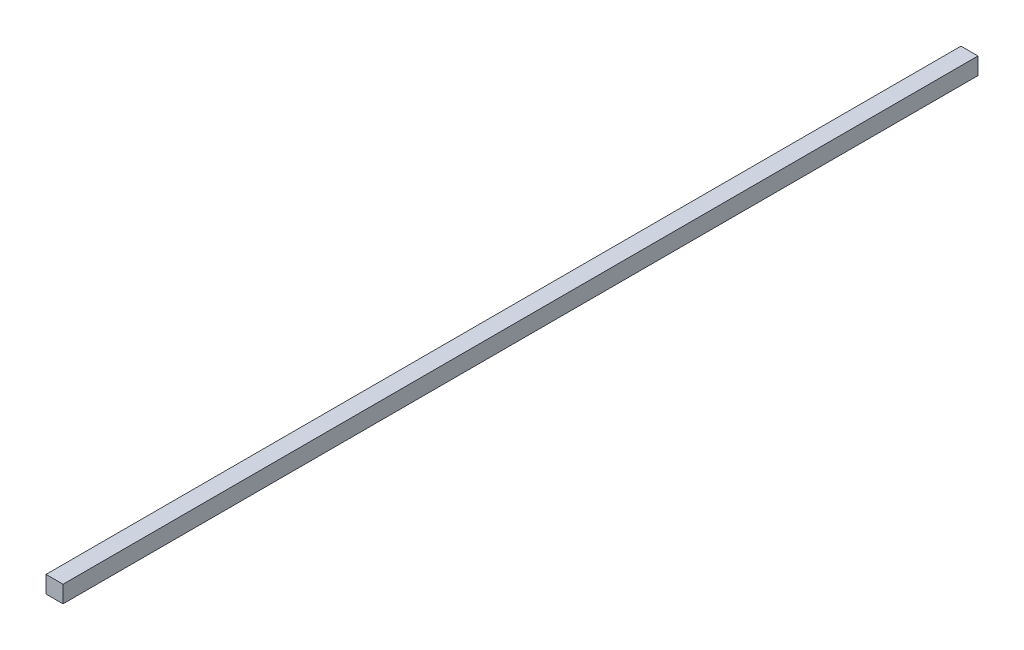
SolidWorks part; units mm, degrees
ref_plane "Front Plane" through (0, 0, 0) normal (0, 0, 1) x (1, 0, 0)
ref_plane "Top Plane" through (0, 0, 0) normal (0, 1, 0) x (1, 0, 0)
ref_plane "Right Plane" through (0, 0, 0) normal (1, 0, 0) x (0, 0, -1)
sketch "Sketch2" plane through (0, 0, 0) normal (0, 0, 1) x (1, 0, 0)
  circle A0 centre (0, 0) radius 1.25
  dimension "D1" = 2.5
sketch "Sketch3" plane through (0, 0, 0) normal (0, 0, 1) x (1, 0, 0)
  line L1 (0.8839, -0.8839) -> (-0.8839, -0.8839)
  line L2 (0.8839, -0.8839) -> (0.8839, 0.8839)
  line L3 (0.8839, 0.8839) -> (-0.8839, 0.8839)
  line L4 (-0.8839, -0.8839) -> (-0.8839, 0.8839)
  line L5 (0.8839, -0.8839) -> (-0.8839, 0.8839) construction
  line L6 (0.8839, 0.8839) -> (-0.8839, -0.8839) construction
  circle A0 centre (0, 0) radius 1.25 construction
  point P0 (0, 0)
extrude "Boss-Extrude1" add sketch "Sketch3" along normal blind 95
